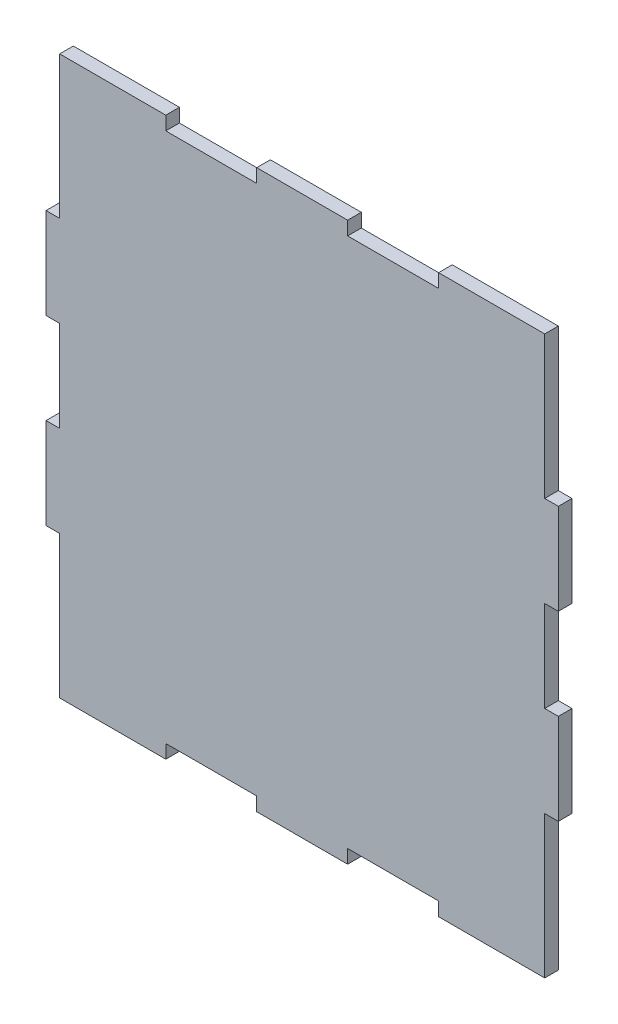
SolidWorks part; units mm, degrees
ref_plane "Front Plane" through (0, 0, 0) normal (0, 0, 1) x (1, 0, 0)
ref_plane "Top Plane" through (0, 0, 0) normal (0, 1, 0) x (1, 0, 0)
ref_plane "Right Plane" through (0, 0, 0) normal (1, 0, 0) x (0, 0, -1)
sketch "Sketch1" plane through (0, 0, 0) normal (0, 0, 1) x (1, 0, 0)
  line L8 (151, 355.5) -> (151, 0) construction
  line L9 (121, 5.5) -> (121, -3.5)
  line L10 (181, 5.5) -> (181, -3.5)
  line L11 (61, 5.5) -> (61, -3.5)
  line L12 (241, 5.5) -> (241, -3.5)
  line L13 (5.5, 180.5) -> (325.5, 180.5) construction
  line L14 (241, 355.5) -> (241, 364.5)
  line L15 (181, 355.5) -> (181, 364.5)
  line L16 (61, 355.5) -> (61, 364.5)
  line L17 (121, 355.5) -> (121, 364.5)
  line L18 (-18, 270.5) -> (-9, 270.5)
  line L19 (311, 210.5) -> (311, 150.5)
  line L20 (-9, 210.5) -> (-18, 210.5)
  line L21 (-9, 150.5) -> (-18, 150.5)
  line L22 (-18, 90.5) -> (-9, 90.5)
  line L23 (320, 90.5) -> (311, 90.5)
  line L24 (311, 150.5) -> (320, 150.5)
  line L25 (311, 210.5) -> (320, 210.5)
  line L26 (320, 270.5) -> (320, 210.5)
  line L27 (320, 270.5) -> (311, 270.5)
  line L30 (-9, 364.5) -> (61, 364.5)
  line L32 (-18, 150.5) -> (-18, 90.5)
  line L33 (-9, 5.5) -> (-9, -3.5)
  line L37 (241, 364.5) -> (311, 364.5)
  line L39 (181, 355.5) -> (241, 355.5)
  line L42 (320, 150.5) -> (320, 90.5)
  line L44 (241, -3.5) -> (311, -3.5)
  line L48 (181, 5.5) -> (241, 5.5)
  line L52 (-9, 90.5) -> (-9, 5.5)
  line L54 (311, 90.5) -> (311, 9.67)
  line L60 (-9, -3.5) -> (61, -3.5)
  line L63 (61, 355.5) -> (121, 355.5)
  line L64 (-9, 364.5) -> (-9, 270.5)
  line L65 (61, 5.5) -> (121, 5.5)
  line L66 (311, 364.5) -> (311, 270.5)
  line L68 (311, 9.67) -> (311, -3.5)
  line L70 (121, -3.5) -> (181, -3.5)
  line L71 (121, 364.5) -> (181, 364.5)
  line L72 (-9, 210.5) -> (-9, 150.5)
  line L73 (-18, 270.5) -> (-18, 210.5)
  dimension "D1" = 320
  dimension "D2" = 350
  dimension "D4" = 60
  dimension "D5" = 30
  dimension "D6" = 60
  dimension "D7" = 30
  dimension "D8" = 9
  dimension "D9" = 9
extrude "Boss-Extrude1" add sketch "Sketch1" along normal blind 9
